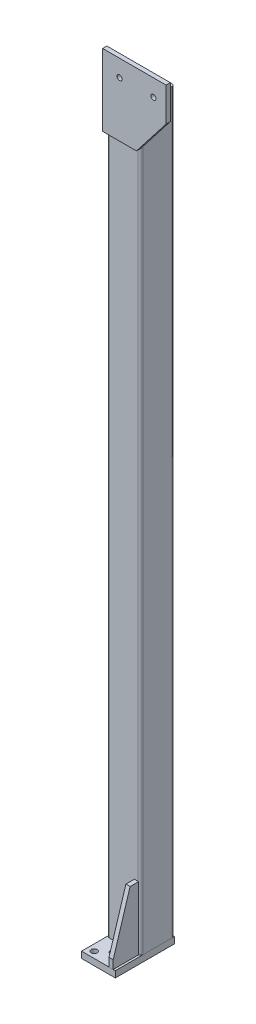
SolidWorks part; units mm, degrees
material "Q235A"
ref_plane "前视基准面" through (0, 0, 0) normal (0, 0, 1) x (1, 0, 0)
ref_plane "上视基准面" through (0, 0, 0) normal (0, 1, 0) x (1, 0, 0)
ref_plane "右视基准面" through (0, 0, 0) normal (1, 0, 0) x (0, 0, -1)
other "Q235A"
sketch "草图1" plane through (0, 0, 0) normal (0, 0, 1) x (1, 0, 0)
  line L0 (0, 1745) -> (0, 0)
  dimension "D2" = 1745
other "结构构件1"
ref_plane "基准面1" through (0, 1745, 0) normal (0, -1, 0) x (0, 0, 1)
sketch "Sketch11" plane through (0, 1745, 0) normal (0, -1, 0) x (0, 0, 1)
  line L0 (-34, -36) -> (34, -36)
  line L1 (-36, -34) -> (-36, 34)
  line L2 (34, 36) -> (-34, 36)
  line L3 (36, 34) -> (36, -34)
  line L4 (-34, -40) -> (34, -40)
  line L5 (-40, -34) -> (-40, 34)
  line L6 (34, 40) -> (-34, 40)
  line L7 (40, 34) -> (40, -34)
  arc A0 (40, 34) -> (34, 40) centre (34, 34) ccw
  arc A1 (34, -40) -> (40, -34) centre (34, -34) ccw
  arc A2 (-40, -34) -> (-34, -40) centre (-34, -34) ccw
  arc A3 (-34, 40) -> (-40, 34) centre (-34, 34) ccw
  arc A4 (-34, 36) -> (-36, 34) centre (-34, 34) ccw
  arc A5 (36, 34) -> (34, 36) centre (34, 34) ccw
  arc A6 (34, -36) -> (36, -34) centre (34, -34) ccw
  arc A7 (-36, -34) -> (-34, -36) centre (-34, -34) ccw
  point P0 (-40, 0)
  point P1 (40, 0)
  point P2 (0, 40)
  point P3 (0, -40)
  point P4 (0, 0)
  point P5 (-40, -40)
  point P6 (40, -40)
  point P7 (40, 40)
  point P8 (-40, 40)
  point P33 (0, 0)
  dimension "D1" = 6
  dimension "Thickness" = 4
  dimension "V_leg" = 80
sketch "草图4" plane through (0, 0, 0) normal (0, -1, 0) x (1, 0, 0)
  line L0 (-34, -40) -> (34, -40) construction
  line L1 (40, -34) -> (40, 34) construction
  line L5 (-40, 100) -> (40, 100)
  line L6 (-40, 100) -> (-40, -40)
  line L7 (-40, -40) -> (40, -40)
  line L8 (40, 100) -> (40, -40)
  dimension "D1" = 80
  dimension "D2" = 140
extrude "凸台-拉伸1" add sketch "草图4" along normal blind 15 separate body
hole_wizard "Ø14.0 (14) 直径孔1" positions "草图13" profile "草图12" hole size "Ø14.0" standard "GB"
sketch "草图13" plane through (0, 0, 0) normal (0, 1, 0) x (-1, 0, 0)
  line L0 (-40, 100) -> (40, 100) construction
  line L1 (40, 100) -> (40, -40) construction
  point P0 (25, 85)
  point P1 (0, 65)
  dimension "D1" = 15
  dimension "D2" = 15
  dimension "D3" = 20
  dimension "D4" = 25
sketch "草图12" plane through (-25, 0, 85) normal (1, 0, 0) x (0, 0, 1)
  line L0 (0, 0) -> (0, 44.206)
  line L1 (0, 44.206) -> (7, 40)
  line L2 (7, 40) -> (7, 0)
  line L5 (7, 0) -> (0, 0)
  line L10 (0, 44.206) -> (-7, 40) construction
  line L11 (0, -6.35) -> (0, 107.95) construction
  dimension "孔直径" = 14
  dimension "孔深度" = 40
  dimension "导头角度" = 118
ref_plane "基准面2" through (25, 0, 0) normal (1, 0, 0) x (0, 0, -1)
sketch "草图11" plane through (25, 0, 0) normal (1, 0, 0) x (0, 0, -1)
  line L0 (40, 0) -> (-100, 0) construction
  line L1 (-100, 20) -> (-60, 150)
  line L2 (-100, -15) -> (-100, 0) construction
  line L7 (-100, 20) -> (-100, 0)
  line L8 (-100, 0) -> (-40, 0)
  line L9 (-40, 0) -> (-40, 150)
  line L10 (-40, 150) -> (-60, 150)
  dimension "D1" = 20
  dimension "D2" = 150
  dimension "D3" = 20
  dimension "D4" = 60
extrude "凸台-拉伸2" add sketch "草图11" along normal blind 10 separate body
sketch "草图22" plane through (0, 0, 40) normal (0, 0, 1) x (1, 0, 0)
  line L0 (-40, 1655) -> (-40, 1825)
  line L1 (-40, 0) -> (-40, 1745) construction
  line L2 (-40, 1825) -> (110, 1825)
  line L3 (110, 1825) -> (110, 1745)
  line L4 (110, 1745) -> (40, 1655)
  line L5 (40, 0) -> (40, 1745) construction
  line L6 (40, 1655) -> (-40, 1655)
  line L7 (34, 1745) -> (-34, 1745) construction
  dimension "D1" = 170
  dimension "D2" = 90
  dimension "D3" = 80
  dimension "D4" = 80
  dimension "D5" = 150
extrude "凸台-拉伸3" add sketch "草图22" along normal blind 10 separate body
hole_wizard "M10 间隙孔1" positions "草图30" profile "草图29" hole size "M10" standard "GB"
sketch "草图30" plane through (0, 0, 40) normal (0, 0, -1) x (-1, 0, 0)
  line L0 (-110, 1825) -> (40, 1825) construction
  line L1 (40, 1825) -> (40, 1655) construction
  point P6 (-80, 1785)
  point P8 (0, 1785)
  dimension "D1" = 40
  dimension "D2" = 40
  dimension "D3" = 80
sketch "草图29" plane through (80, 1785, 40) normal (1, 0, 0) x (0, 1, 0)
  line L0 (0, 0) -> (0, 33.6052)
  line L1 (0, 33.6052) -> (6, 30)
  line L2 (6, 30) -> (6, 0)
  line L5 (6, 0) -> (0, 0)
  line L10 (0, 33.6052) -> (-6, 30) construction
  line L11 (0, -6.35) -> (0, 107.95) construction
  dimension "孔直径" = 12
  dimension "孔深度" = 30
  dimension "导头角度" = 118
hole_wizard "M8 螺纹孔2" positions "草图34" profile "草图33" tap size "M8" standard "GB"
sketch "草图34" plane through (-40, 0, 0) normal (-1, 0, 0) x (0, 0, 1)
  line L4 (-20, 655) -> (-20, 675) construction
  line L5 (-20, 1325) -> (-20, 1345) construction
  line L6 (-20, 1005) -> (-20, 1025) construction
  line L7 (-20, 1955) -> (-20, 1975) construction
  line L8 (-20, 1585) -> (-20, 1605) construction
  point P21 (-20, 665)
  point P24 (-20, 1335)
  point P28 (-20, 1015)
  point P31 (-20, 1965)
  point P34 (-20, 1595)
  dimension "D1" = 20
  dimension "D2" = 20
  dimension "D3" = 20
  dimension "D4" = 20
  dimension "D5" = 20
sketch "草图33" plane through (-40, 665, -20) normal (0, 1, 0) x (0, 0, 1)
  line L0 (0, 0) -> (0, 21.7929)
  line L1 (0, 21.7929) -> (3.4, 19.75)
  line L2 (3.4, 19.75) -> (3.4, 0)
  line L5 (3.4, 0) -> (0, 0)
  line L10 (0, 21.7929) -> (-3.4, 19.75) construction
  line L11 (0, -6.35) -> (0, 107.95) construction
  dimension "螺纹孔钻头直径" = 6.8
  dimension "螺纹孔钻头深度" = 19.75
  dimension "导头角度" = 118
cosmetic thread "孔螺蚊线23" parameters "D1"=4, "D2"=8
cosmetic thread "孔螺蚊线24" parameters "D1"=4, "D2"=8
cosmetic thread "孔螺蚊线34" parameters "D1"=4, "D2"=8
cosmetic thread "孔螺蚊线37" parameters "D1"=4, "D2"=8
hole_wizard "M8 螺纹孔6" [suppressed] positions "草图42" profile "草图41" tap size "M8" standard "GB"
sketch "草图42" plane through (0, 0, 40) normal (0, 0, 1) x (1, 0, 0)
  line L0 (-20, 890) -> (-20, 880) construction
  line L2 (-20, 590) -> (-20, 580.3474) construction
  line L4 (-20, 290) -> (-20, 280) construction
  point P0 (-20, 885)
  point P1 (-20, 585.1737)
  point P3 (-20, 285)
sketch "草图41" plane through (-20, 885, 40) normal (1, 0, 0) x (0, -1, 0)
  line L0 (0, 0) -> (0, 21.7929)
  line L1 (0, 21.7929) -> (3.4, 19.75)
  line L2 (3.4, 19.75) -> (3.4, 0)
  line L5 (3.4, 0) -> (0, 0)
  line L10 (0, 21.7929) -> (-3.4, 19.75) construction
  line L11 (0, -6.35) -> (0, 107.95) construction
  dimension "螺纹孔钻头直径" = 6.8
  dimension "螺纹孔钻头深度" = 19.75
  dimension "导头角度" = 118
cosmetic thread "孔螺蚊线29" [suppressed] parameters "D1"=4, "D2"=8
cosmetic thread "孔螺蚊线30" [suppressed] parameters "D1"=4, "D2"=8
cosmetic thread "孔螺蚊线31" [suppressed] parameters "D1"=4, "D2"=8
hole_wizard "M8 螺纹孔7" positions "草图44" profile "草图43" tap size "M8" standard "GB"
sketch "草图44" plane through (-40, 0, 0) normal (-1, 0, 0) x (0, 0, 1)
  point P0 (20, 1117)
  point P3 (20, 317)
sketch "草图43" plane through (-40, 1117, 20) normal (0, 1, 0) x (0, 0, 1)
  line L0 (0, 0) -> (0, 24.2929)
  line L1 (0, 24.2929) -> (3.4, 22.25)
  line L2 (3.4, 22.25) -> (3.4, 0)
  line L5 (3.4, 0) -> (0, 0)
  line L10 (0, 24.2929) -> (-3.4, 22.25) construction
  line L11 (0, -6.35) -> (0, 107.95) construction
  dimension "螺纹孔钻头直径" = 6.8
  dimension "螺纹孔钻头深度" = 22.25
  dimension "导头角度" = 118
cosmetic thread "孔螺蚊线35" parameters "D1"=4, "D2"=8
cosmetic thread "孔螺蚊线36" parameters "D1"=4, "D2"=8
